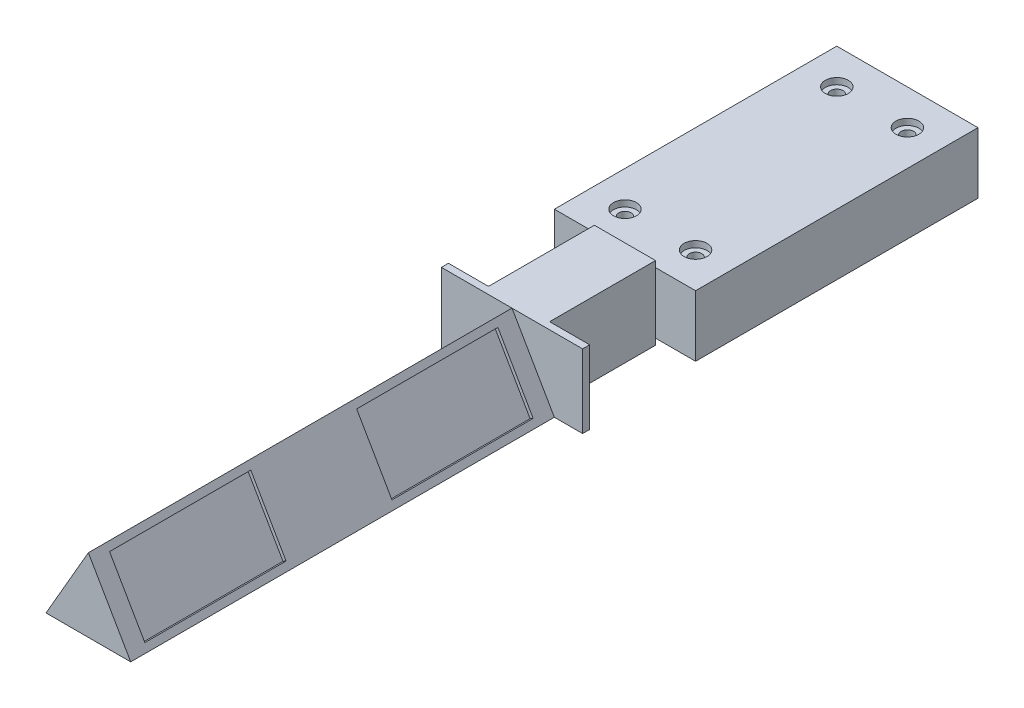
SolidWorks part; units mm, degrees
ref_plane "正面" through (0, 0, 0) normal (0, 0, 1) x (1, 0, 0)
ref_plane "平面" through (0, 0, 0) normal (0, 1, 0) x (1, 0, 0)
ref_plane "右側面" through (0, 0, 0) normal (1, 0, 0) x (0, 0, -1)
sketch "ｽｹｯﾁ2" plane through (0, 0, 0) normal (0, 0, -1) x (-1, 0, 0)
  line L0 (0, 10.3923) -> (0, -10.3923)
  line L2 (20, -10.3923) -> (-20, -10.3923) construction
  line L3 (0, -10.3923) -> (-12, -10.3923)
  line L4 (-12, -10.3923) -> (0, 10.3923)
  line L5 (0, 10.3923) -> (12, -10.3923)
  line L6 (12, -10.3923) -> (0, -10.3923)
extrude "ﾎﾞｽ - 押し出し2" add sketch "ｽｹｯﾁ2" along normal blind 120
sketch "ｽｹｯﾁ3" plane through (0, 0, -120) normal (0, 0, -1) x (-1, 0, 0)
  line L1 (20, 10.3923) -> (-20, 10.3923)
  line L2 (20, 10.3923) -> (20, -10.3923)
  line L3 (20, -10.3923) -> (-20, -10.3923)
  line L4 (-20, 10.3923) -> (-20, -10.3923)
  line L5 (20, 10.3923) -> (-20, -10.3923) construction
  line L6 (20, -10.3923) -> (-20, 10.3923) construction
  point P0 (0, 0)
extrude "ﾎﾞｽ - 押し出し3" add sketch "ｽｹｯﾁ3" along normal blind 2
sketch "ｽｹｯﾁ4" plane through (0, 0, -122) normal (0, 0, -1) x (-1, 0, 0)
  line L0 (-20, -10.3923) -> (20, -10.3923) construction
  line L1 (8.6603, 10.3923) -> (-8.6603, 10.3923)
  line L2 (8.6603, 10.3923) -> (8.6603, -10.3923)
  line L3 (8.6603, -10.3923) -> (-8.6603, -10.3923)
  line L4 (-8.6603, 10.3923) -> (-8.6603, -10.3923)
  line L5 (8.6603, 10.3923) -> (-8.6603, -10.3923) construction
  line L6 (8.6603, -10.3923) -> (-8.6603, 10.3923) construction
  point P0 (0, 0)
  dimension "D1" = 17.3205
extrude "ﾎﾞｽ - 押し出し4" add sketch "ｽｹｯﾁ4" along normal blind 30
sketch "ｽｹｯﾁ5" plane through (0, 0, -152) normal (0, 0, -1) x (-1, 0, 0)
  line L1 (20, 8.6603) -> (-20, 8.6603)
  line L2 (20, 8.6603) -> (20, -8.6603)
  line L3 (20, -8.6603) -> (-20, -8.6603)
  line L4 (-20, 8.6603) -> (-20, -8.6603)
  line L5 (20, 8.6603) -> (-20, -8.6603) construction
  line L6 (20, -8.6603) -> (-20, 8.6603) construction
  point P0 (0, 0)
extrude "ﾎﾞｽ - 押し出し5" add sketch "ｽｹｯﾁ5" along normal blind 80
sketch "ｽｹｯﾁ6" plane through (0, 10.3923, 0) normal (0, 1, 0) x (1, 0, 0)
  line L0 (0, 120) -> (0, 232)
  line L1 (-20, 232) -> (20, 232) construction
  line L2 (-20, 152) -> (-8.6603, 152) construction
  circle A0 centre (-10, 162) radius 1.75
  circle A1 centre (10, 162) radius 1.75
  circle A2 centre (-10, 222) radius 1.75
  circle A3 centre (10, 222) radius 1.75
  dimension "D1" = 3.5
  dimension "D2" = 3.5
  dimension "D3" = 3.5
  dimension "D4" = 3.5
  dimension "D8" = 0
  dimension "D9" = 0
  dimension "D10" = 10
  dimension "D11" = 0
  dimension "D12" = 0
  dimension "D5" = 10
  dimension "D6" = 10
  dimension "D7" = 10
extrude "ｶｯﾄ - 押し出し1" cut sketch "ｽｹｯﾁ6" against normal through all contours A2 | A0 | A1 | A3
sketch "ｽｹｯﾁ7" plane through (0, 10.3923, 0) normal (0, 1, 0) x (1, 0, 0)
  circle A0 centre (-10, 162) radius 3.25
  circle A1 centre (-10, 222) radius 3.25
  circle A2 centre (10, 222) radius 3.25
  circle A3 centre (10, 162) radius 3.25
  dimension "D1" = 6.5
  dimension "D2" = 6.5
  dimension "D3" = 6.5
  dimension "D4" = 6.5
extrude "ｶｯﾄ - 押し出し2" cut sketch "ｽｹｯﾁ7" against normal blind 3.5
fillet "ﾌｨﾚｯﾄ2" [suppressed] radius 0.5
fillet "ﾌｨﾚｯﾄ3" [suppressed] radius 5
fillet "ﾌｨﾚｯﾄ4" [suppressed] radius 5
fillet "ﾌｨﾚｯﾄ5" [suppressed] radius 5
sketch "ｽｹｯﾁ8" plane through (-4.5, 2.5981, 0) normal (-0.866, 0.5, 0) x (0, 0, 1)
  line L0 (-120, 9) -> (-120, -15) construction
  line L1 (-115, 7) -> (-75, 7)
  line L2 (-115, 7) -> (-115, -13)
  line L3 (-115, -13) -> (-75, -13)
  line L4 (-75, 7) -> (-75, -13)
  line L5 (-120, 9) -> (0, 9) construction
  line L6 (-120, -15) -> (0, -15) construction
  line L7 (-60, 9) -> (-60, -15) construction
  line L8 (-5, -13) -> (-45, -13)
  line L9 (-5, 7) -> (-5, -13)
  line L10 (-5, 7) -> (-45, 7)
  line L11 (-45, 7) -> (-45, -13)
  dimension "D1" = 5
  dimension "D2" = 2
  dimension "D3" = 2
  dimension "D4" = 40
extrude "ｶｯﾄ - 押し出し3" cut sketch "ｽｹｯﾁ8" against normal blind 1
sketch "ｽｹｯﾁ10" plane through (4.5, 2.5981, 0) normal (0.866, 0.5, 0) x (0, 0, -1)
  line L0 (0, -15) -> (0, 9) construction
  line L1 (5, 7) -> (45, 7)
  line L2 (5, 7) -> (5, -13)
  line L3 (5, -13) -> (45, -13)
  line L4 (45, 7) -> (45, -13)
  line L5 (120, 9) -> (0, 9) construction
  line L6 (60, 9) -> (60, -15) construction
  line L7 (120, -15) -> (0, -15) construction
  line L8 (115, 7) -> (115, -13)
  line L9 (115, -13) -> (75, -13)
  line L10 (115, 7) -> (75, 7)
  line L11 (75, 7) -> (75, -13)
  dimension "D1" = 5
  dimension "D2" = 40
  dimension "D3" = 2
  dimension "D4" = 20
extrude "ｶｯﾄ - 押し出し4" cut sketch "ｽｹｯﾁ10" against normal blind 1
sketch "ｽｹｯﾁ11" plane through (0, -10.3923, 0) normal (0, -1, 0) x (-1, 0, 0)
  line L0 (-12, 0) -> (12, 0)
  line L1 (12, 120) -> (12, 0) construction
  line L2 (-10, 5) -> (10, 5)
  line L3 (-10, 5) -> (-10, 45)
  line L4 (-10, 45) -> (10, 45)
  line L5 (10, 5) -> (10, 45)
  line L6 (-12, 60) -> (12, 60) construction
  line L7 (-12, 120) -> (-12, 0) construction
  line L8 (10, 115) -> (10, 75)
  line L9 (-10, 115) -> (10, 115)
  line L10 (-10, 115) -> (-10, 75)
  line L11 (-10, 75) -> (10, 75)
  dimension "D1" = 5
  dimension "D2" = 40
  dimension "D3" = 2
  dimension "D4" = 20
  dimension "D5" = 60
extrude "ｶｯﾄ - 押し出し5" cut sketch "ｽｹｯﾁ11" against normal blind 1 contours L2 L5 L4 L3 | L10 L11 L8 L9
